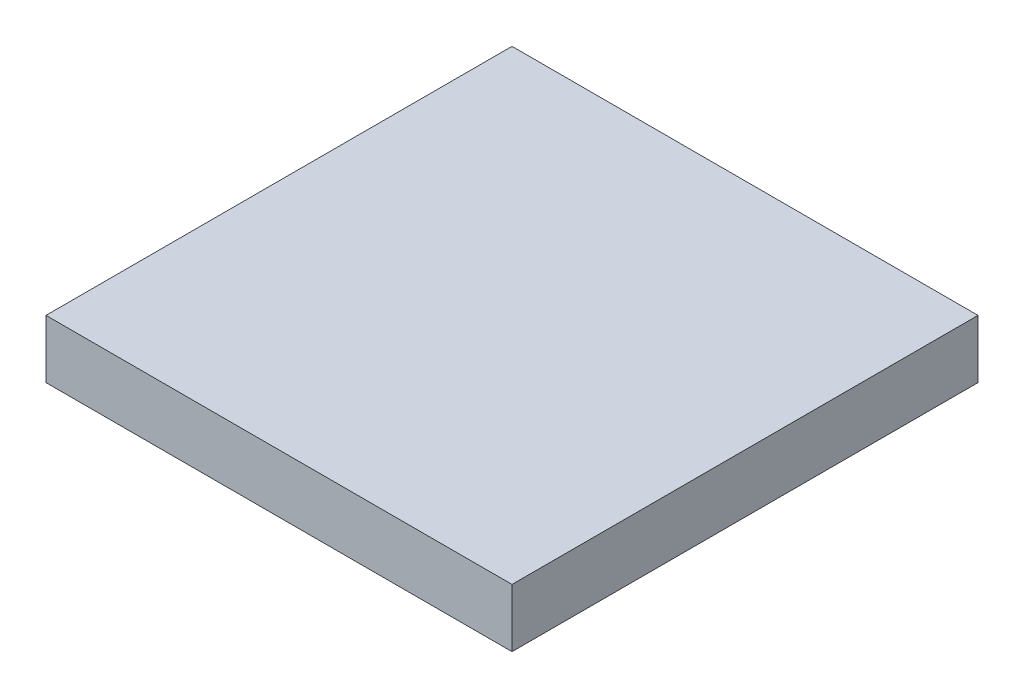
SolidWorks part; units mm, degrees
ref_plane "Front Plane" through (0, 0, 0) normal (0, 0, 1) x (1, 0, 0)
ref_plane "Top Plane" through (0, 0, 0) normal (0, 1, 0) x (1, 0, 0)
ref_plane "Right Plane" through (0, 0, 0) normal (1, 0, 0) x (0, 0, -1)
other "Configuration Table"
sketch "Sketch1" plane through (0, 0, 0) normal (0, 0, 1) x (1, 0, 0)
  line L1 (150, 1800) -> (550, 1800)
  line L2 (150, 1800) -> (150, 1850)
  line L3 (150, 1850) -> (550, 1850)
  line L4 (550, 1800) -> (550, 1850)
extrude "OVEN_karbon_filtre_40x40x5_opsiyon_1" add sketch "Sketch1" against normal blind 400 from offset 100 separate body
